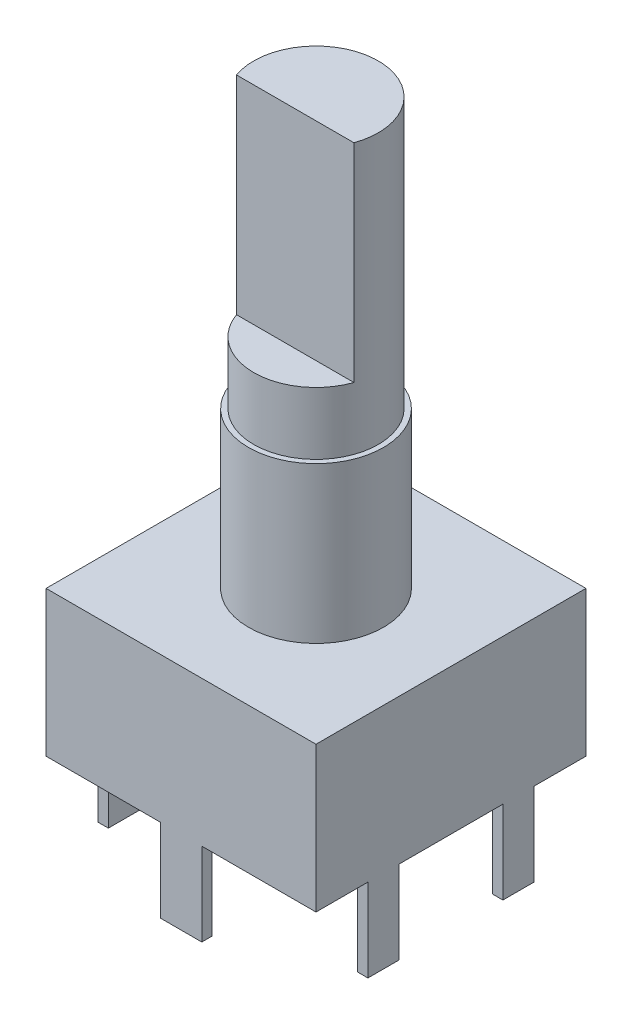
SolidWorks part; units mm, degrees
ref_plane "Front Plane" through (0, 0, 0) normal (0, 0, 1) x (1, 0, 0)
ref_plane "Top Plane" through (0, 0, 0) normal (0, 1, 0) x (1, 0, 0)
ref_plane "Right Plane" through (0, 0, 0) normal (1, 0, 0) x (0, 0, -1)
sketch "Sketch1" plane through (0, 0, 0) normal (0, 1, 0) x (1, 0, 0)
  line L1 (-12, 0) -> (0, 0)
  line L2 (-12, 0) -> (-12, -12)
  line L3 (-12, -12) -> (0, -12)
  line L4 (0, 0) -> (0, -12)
  point P4 (0, 0)
  dimension "D1" = 12
  dimension "D2" = 12
extrude "Boss-Extrude1" add sketch "Sketch1" along normal blind 7
sketch "Sketch2" plane through (0, 0, 0) normal (0, -1, 0) x (1, 0, 0)
  line L0 (-12.5, 10) -> (-12.5, 8.5)
  line L1 (-7, -0.5) -> (-5, -0.5)
  line L2 (0.5, 2) -> (0.5, 3.5)
  line L3 (-5, 12.5) -> (-7, 12.5)
  line L4 (-12, 12) -> (-12, 0)
  line L5 (-12, 0) -> (0, 0)
  line L6 (0, 0) -> (0, 12)
  line L7 (0, 12) -> (-12, 12)
  line L8 (-12, 12) -> (-12, 10) construction
  line L9 (-12, 0) -> (-7, 0) construction
  line L10 (0, 0) -> (0, 2) construction
  line L11 (0, 12) -> (-5, 12) construction
  line L12 (-12, 10) -> (-12.5, 10)
  line L13 (-12, 8.5) -> (-12.5, 8.5)
  line L14 (-12, 6.793) -> (-12.5, 6.793)
  line L15 (-12, 5.293) -> (-12.5, 5.293)
  line L16 (-12, 3.5) -> (-12.5, 3.5)
  line L17 (-12, 2) -> (-12.5, 2)
  line L18 (-12.5, 6.793) -> (-12.5, 5.293)
  line L19 (-12, 6.793) -> (-12, 5.293)
  line L20 (-12.5, 12.5) -> (-12.5, -0.5) construction
  line L21 (-12.5, 3.5) -> (-12.5, 2)
  line L22 (-12, 12) -> (-12, 0) construction
  line L23 (-12, 3.5) -> (-12, 2)
  line L24 (-12, 10) -> (-12, 8.5)
  line L25 (-12, 2) -> (-12, 0) construction
  line L26 (0, 10) -> (0.5, 10)
  line L27 (0, 8.5) -> (0.5, 8.5)
  line L28 (0.5, 3.5) -> (0, 3.5)
  line L29 (0, 2) -> (0, 3.5)
  line L30 (0, 2) -> (0.5, 2)
  line L31 (0, 8.5) -> (0, 10)
  line L32 (0.5, 8.5) -> (0.5, 10)
  line L33 (0, 0) -> (0, 12) construction
  line L34 (-7, 12.5) -> (-7, 12)
  line L35 (0.5, -0.5) -> (0.5, 12.5) construction
  line L36 (-7, 12) -> (-12, 12) construction
  line L37 (-5, 12.5) -> (-5, 12)
  line L38 (-5, 0) -> (-5, -0.5)
  line L39 (0.5, 12.5) -> (-12.5, 12.5) construction
  line L40 (-7, 0) -> (-7, -0.5)
  line L41 (0, 12) -> (-12, 12) construction
  line L42 (-12.5, -0.5) -> (0.5, -0.5) construction
  line L43 (-5, 12) -> (-7, 12)
  line L44 (-7, 0) -> (-5, 0)
  line L45 (-12, 0) -> (0, 0) construction
  line L46 (-5, 0) -> (0, 0) construction
  line L47 (-12, 0) -> (-12, 12) construction
  line L48 (0, 0) -> (-12, 0) construction
  line L49 (0, 10) -> (0, 12) construction
  point P28 (-1.4354, 1.8349)
  point P34 (-0.4453, 10.4691)
  dimension "D3" = 2
  dimension "D4" = 1.5
  dimension "D5" = 5.207
  dimension "D6" = 1.5
  dimension "D7" = 2
  dimension "D8" = 1.5
  dimension "D9" = 2
  dimension "D10" = 1.5
  dimension "D11" = 1.5
  dimension "D12" = 2
  dimension "D13" = 2
  dimension "D14" = 5
  dimension "D1" = 0
  dimension "D2" = 0.5
extrude "Boss-Extrude2" add sketch "Sketch2" along normal blind 4
sketch "Sketch3" plane through (0, 7, 0) normal (0, 1, 0) x (1, 0, 0)
  line L0 (0.5, 0.5) -> (-12.5, 0.5)
  line L1 (-12.5, 0.5) -> (-12.5, -12.5)
  line L2 (-12.5, -12.5) -> (0.5, -12.5)
  line L3 (0.5, -12.5) -> (0.5, 0.5)
  line L4 (-12, 0) -> (-12, -12)
  line L5 (-12, -12) -> (0, -12)
  line L6 (0, -12) -> (0, 0)
  line L7 (0, 0) -> (-12, 0)
  line L8 (-12, 0) -> (-12, -12)
  line L9 (-12, -12) -> (0, -12)
  line L10 (0, -12) -> (0, 0)
  line L11 (0, 0) -> (-12, 0)
  dimension "D1" = 0
  dimension "D2" = 0.5
extrude "Boss-Extrude3" add sketch "Sketch3" against normal up to surface (7 mm away) up to face at (-12.25, 0, 2.75)
sketch "Sketch4" plane through (0, 7, 0) normal (0, 1, 0) x (1, 0, 0)
  line L0 (-6, 0.5) -> (-6, -12.5) construction
  line L1 (0.5, 0.5) -> (-12.5, 0.5) construction
  line L2 (-12.5, -12.5) -> (0.5, -12.5) construction
  line L3 (-12.5, -6) -> (0.5, -6) construction
  line L4 (-12.5, 0.5) -> (-12.5, -12.5) construction
  line L5 (0.5, -12.5) -> (0.5, 0.5) construction
  circle A0 centre (-6, -6) radius 3.25
  point P12 (-6, -6)
  dimension "D1" = 6.5
extrude "Boss-Extrude4" add sketch "Sketch4" along normal blind 7.5
sketch "Sketch5" plane through (0, 14.5, 0) normal (0, 1, 0) x (1, 0, 0)
  circle A0 centre (-6, -6) radius 3
  circle A1 centre (-6, -6) radius 3.25
  circle A2 centre (-6, -6) radius 3.25 construction
  dimension "D2" = 6
  dimension "D1" = 0
extrude "Boss-Extrude5" add sketch "Sketch5" along normal blind 13
sketch "Sketch6" plane through (0, 27.5, 0) normal (0, 1, 0) x (1, 0, 0)
  line L0 (-8.8284, -7) -> (-3.1716, -7)
  circle A1 centre (-6, -6) radius 3
  arc A2 (-8.8284, -7) -> (-3.1716, -7) centre (-6, -6) ccw
  dimension "D2" = 1
  dimension "D1" = 0
extrude "Cut-Extrude1" cut sketch "Sketch6" against normal blind 10
